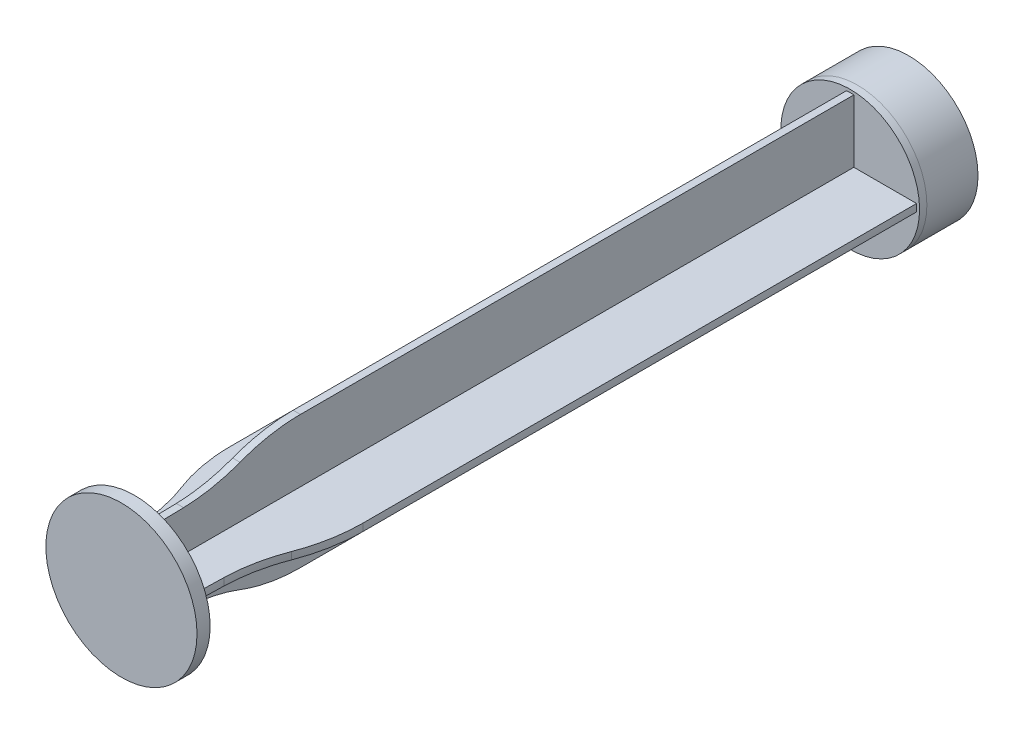
SolidWorks part; units mm, degrees
ref_plane "Front Plane" through (0, 0, 0) normal (0, 0, 1) x (1, 0, 0)
ref_plane "Top Plane" through (0, 0, 0) normal (0, 1, 0) x (1, 0, 0)
ref_plane "Right Plane" through (0, 0, 0) normal (1, 0, 0) x (0, 0, -1)
sketch "Sketch1" plane through (0, 0, 0) normal (0, 0, 1) x (1, 0, 0)
  circle A0 centre (0, 0) radius 9.5
  dimension "D1" = 19
extrude "Boss-Extrude1" add sketch "Sketch1" along normal blind 1
sketch "Sketch2" plane through (0, 0, 1) normal (0, 0, 1) x (1, 0, 0)
  line L0 (-0.5, 9.1) -> (0.5, 9.1)
  line L1 (0.5, 9.1) -> (0.5, 0.5)
  line L2 (0.5, 0.5) -> (9.1, 0.5)
  line L3 (9.1, 0.5) -> (9.1, -0.5)
  line L4 (9.1, -0.5) -> (0.5, -0.5)
  line L5 (0.5, -0.5) -> (0.5, -9.1)
  line L6 (0.5, -9.1) -> (-0.5, -9.1)
  line L7 (-0.5, -9.1) -> (-0.5, -0.5)
  line L8 (-0.5, -0.5) -> (-9.1, -0.5)
  line L9 (-9.1, -0.5) -> (-9.1, 0.5)
  line L10 (-9.1, 0.5) -> (-0.5, 0.5)
  line L11 (-0.5, 0.5) -> (-0.5, 9.1)
  line L12 (0, 9.1) -> (0, 0) construction
  line L13 (0, 0) -> (9.1, 0) construction
  dimension "D1" = 18.2
  dimension "D2" = 1
extrude "Boss-Extrude2" add sketch "Sketch2" along normal blind 98
sketch "Sketch3" plane through (0, 0, 99) normal (0, 0, 1) x (1, 0, 0)
  circle A0 centre (0, 0) radius 10.35
  dimension "D1" = 20.7
extrude "Boss-Extrude3" add sketch "Sketch3" along normal blind 1.8
sketch "Sketch4" plane through (0, 0, 0) normal (1, 0, 0) x (0, 0, -1)
  line L0 (-99, 0) -> (-99, 5.9) construction
  line L1 (-99, 5.9) -> (-99, 9.1)
  line L2 (-99, 9.1) -> (-76.8, 9.1) construction
  line L3 (-76.8, 9.1) -> (-1, 9.1)
  line L4 (-99, 0) -> (0, 0) construction
  line L5 (-99, 5.9) -> (-92.8, 6.05)
  line L6 (-99, 9.1) -> (-99, 10.35)
  line L7 (-99, 10.35) -> (-1, 10.35)
  line L8 (-1, 10.35) -> (-1, 9.1)
  arc A0 (-92.8, 6.05) -> (-85.0805, 7.5716) centre (-93.361, 29.2384) ccw
  arc A1 (-85.0805, 7.5716) -> (-76.8, 9.1) centre (-76.8, -14.0952) cw
  dimension "D1" = 11.8
  dimension "D2" = 12.1
  dimension "D3" = 6.2
  dimension "D4" = 16
revolve "Cut-Revolve1" cut sketch "Sketch4" angle 360 about L4
sketch "Sketch6" plane through (0, 0, 0) normal (1, 0, 0) x (0, 0, -1)
  line L0 (0, 0) -> (0, 9.5)
  line L1 (0, 9.5) -> (7, 9.5)
  line L2 (7, 9.5) -> (9.0349, 0)
  line L3 (0, 0) -> (9.0349, 0)
  point P2 (0, 0)
  dimension "D1" = 77.91
  dimension "D2" = 7
revolve "Revolve1" add sketch "Sketch6" angle 360 about L3
